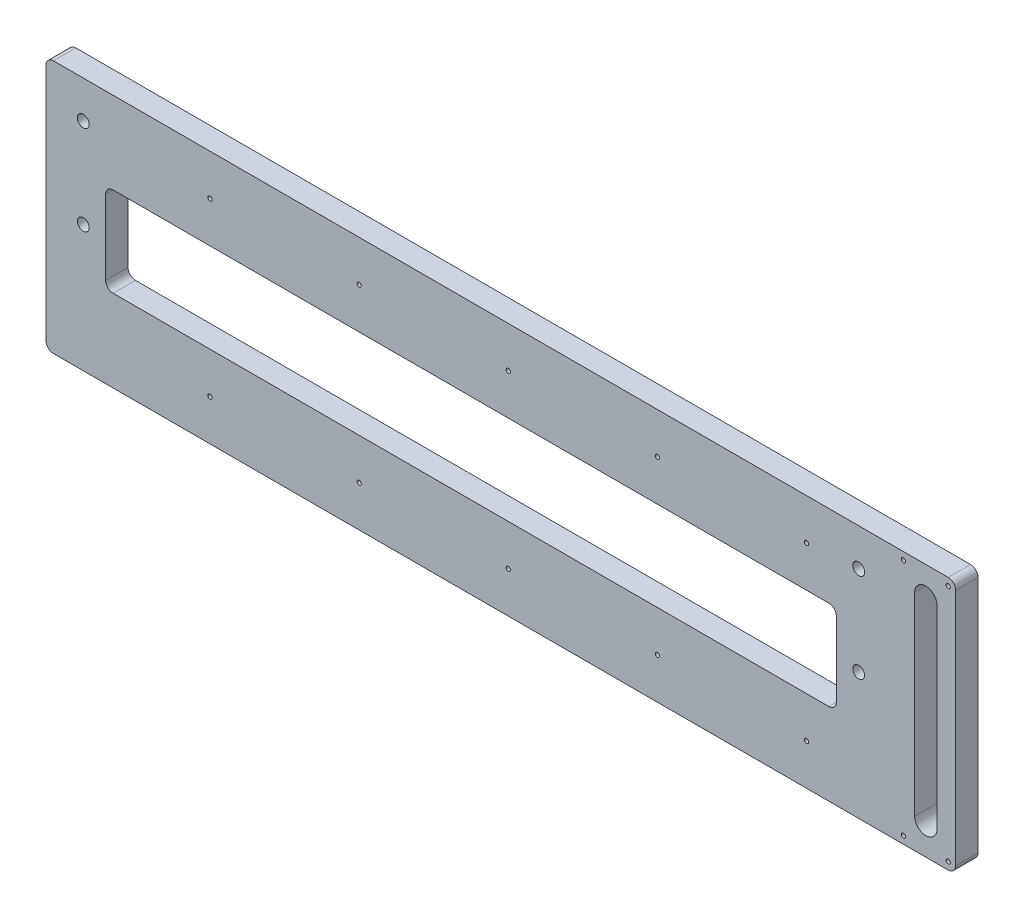
SolidWorks part; units mm, degrees
ref_plane "Front Plane" through (0, 0, 0) normal (0, 0, 1) x (1, 0, 0)
ref_plane "Top Plane" through (0, 0, 0) normal (0, 1, 0) x (1, 0, 0)
ref_plane "Right Plane" through (0, 0, 0) normal (1, 0, 0) x (0, 0, -1)
sketch "Sketch2" plane through (0, 0, 0) normal (0, 0, 1) x (1, 0, 0)
  line L0 (330.2, 107.95) -> (330.2, -107.95)
  line L1 (-393.7, -107.95) -> (330.2, -107.95)
  line L2 (-393.7, -107.95) -> (-393.7, 107.95)
  line L3 (-393.7, 107.95) -> (330.2, 107.95)
  line L5 (-393.7, -107.95) -> (393.7, 107.95) construction
  line L6 (-393.7, 107.95) -> (393.7, -107.95) construction
  point P0 (0, 0)
  dimension "D1" = 787.4
  dimension "D2" = 215.9
extrude "Boss-Extrude1" add sketch "Sketch2" along normal blind 19.05
sketch "Sketch13" plane through (0, 0, 19.05) normal (0, 0, 1) x (1, 0, 0)
  line L1 (-336.55, -38.1) -> (273.05, -38.1)
  line L2 (-342.9, -31.75) -> (-342.9, 31.75)
  line L3 (-336.55, 38.1) -> (273.05, 38.1)
  line L4 (279.4, -31.75) -> (279.4, 31.75)
  line L5 (-342.9, -38.1) -> (279.4, 38.1) construction
  line L6 (-342.9, 38.1) -> (279.4, -38.1) construction
  line L7 (-393.7, 107.95) -> (-393.7, -107.95) construction
  line L9 (330.2, -107.95) -> (330.2, 107.95) construction
  arc A0 (273.05, 38.1) -> (279.4, 31.75) centre (273.05, 31.75) cw
  arc A1 (273.05, -38.1) -> (279.4, -31.75) centre (273.05, -31.75) ccw
  arc A2 (-336.55, -38.1) -> (-342.9, -31.75) centre (-336.55, -31.75) cw
  arc A3 (-342.9, 31.75) -> (-336.55, 38.1) centre (-336.55, 31.75) cw
  point P19 (279.4, 0)
  dimension "D3" = 6.35
  dimension "D1" = 76.2
  dimension "D2" = 50.8
  dimension "D4" = 50.8
extrude "Cut-Extrude3" cut sketch "Sketch13" against normal through all
hole_wizard "#27 (0.144) Diameter Hole1" positions "Sketch14" profile "Sketch15" hole size "#27" standard "ANSI Inch" end condition through all
sketch "Sketch14" plane through (0, 0, 0) normal (0, 0, -1) x (-1, 0, 0)
  line L1 (-254, -73.025) -> (254, -73.025) construction
  line L2 (-254, -73.025) -> (-254, 73.025) construction
  line L3 (-254, 73.025) -> (254, 73.025) construction
  line L4 (254, -73.025) -> (254, 73.025) construction
  line L5 (-254, -73.025) -> (254, 73.025) construction
  line L6 (-254, 73.025) -> (254, -73.025) construction
  point P1 (0, 0)
  point P22 (-254, 73.025)
  point P36 (-127, 73.025)
  point P37 (0, 73.025)
  point P38 (127, 73.025)
  point P39 (254, 73.025)
  point P40 (-127, -73.025)
  point P41 (0, -73.025)
  point P42 (127, -73.025)
  point P43 (254, -73.025)
  point P44 (-254, -73.025)
  dimension "D1" = 146.05
  dimension "D2" = 508
  dimension "D3" = 5
  dimension "D4" = 2
sketch "Sketch15" plane through (0, 0, 0) normal (1, 0, 0) x (0, 1, 0)
  line L0 (0, 0) -> (0, 19.05)
  line L1 (0, 19.05) -> (1.8288, 19.05)
  line L2 (1.8288, 19.05) -> (1.8288, 0)
  line L5 (1.8288, 0) -> (0, 0)
  line L11 (0, -6.35) -> (0, 107.95) construction
  dimension "Thru Hole Dia." = 3.6576
  dimension "Thru Hole Depth" = 19.05
hole_wizard "3/8 Clearance Hole1" positions "Sketch18" profile "Sketch19" hole size "3/8" standard "ANSI Inch" end condition through all
sketch "Sketch18" plane through (0, 0, 0) normal (0, 0, -1) x (-1, 0, 0)
  line L0 (-330.2, -107.95) -> (-330.2, 107.95) construction
  line L1 (-330.2, 107.95) -> (393.7, 107.95) construction
  line L2 (393.7, 107.95) -> (393.7, -107.95) construction
  line L5 (-298.45, 76.2) -> (361.95, 76.2) construction
  line L6 (-298.45, 76.2) -> (-298.45, 0) construction
  line L7 (-298.45, 0) -> (361.95, 0) construction
  line L8 (361.95, 76.2) -> (361.95, 0) construction
  point P0 (-298.45, 76.2)
  point P2 (361.95, 76.2)
  point P73 (361.95, 0)
  point P128 (-298.45, 0)
  dimension "D1" = 31.75
  dimension "D2" = 31.75
  dimension "D3" = 31.75
  dimension "D4" = 31.75
  dimension "D5" = 76.2
sketch "Sketch19" plane through (298.45, 76.2, 0) normal (1, 0, 0) x (0, 1, 0)
  line L0 (0, 0) -> (0, 19.05)
  line L1 (0, 19.05) -> (5.0419, 19.05)
  line L2 (5.0419, 19.05) -> (5.0419, 0)
  line L5 (5.0419, 0) -> (0, 0)
  line L11 (0, -6.35) -> (0, 107.95) construction
  dimension "Thru Hole Dia." = 10.0838
  dimension "Thru Hole Depth" = 19.05
sketch "Sketch22" plane through (330.2, 0, 0) normal (1, 0, 0) x (0, 0, -1)
  line L1 (-19.05, 107.95) -> (0, 107.95)
  line L2 (-19.05, 107.95) -> (-19.05, -107.95)
  line L3 (-19.05, -107.95) -> (0, -107.95)
  line L4 (0, 107.95) -> (0, -107.95)
extrude "Boss-Extrude2" add sketch "Sketch22" along normal blind 50.8
fillet "Fillet1" radius 6.35 4 edges at (-393.7, -107.95, 9.525) (-393.7, 107.95, 9.525) (381, -107.95, 9.525) (381, 107.95, 9.525)
hole_wizard "#6 Clearance Hole1" positions "Sketch23" profile "Sketch24" hole size "#6" standard "ANSI Inch" end condition through all
sketch "Sketch23" plane through (0, 0, 19.05) normal (0, 0, 1) x (1, 0, 0)
  line L0 (355.6, 107.95) -> (355.6, -107.95) construction
  line L1 (374.65, 107.95) -> (-387.35, 107.95) construction
  line L2 (-387.35, -107.95) -> (374.65, -107.95) construction
  line L4 (381, 101.6) -> (381, -101.6) construction
  line L6 (374.65, -101.6) -> (336.55, -101.6) construction
  line L7 (374.65, -101.6) -> (374.65, 101.6) construction
  line L8 (374.65, 101.6) -> (336.55, 101.6) construction
  line L9 (336.55, -101.6) -> (336.55, 101.6) construction
  line L10 (374.65, -101.6) -> (336.55, 101.6) construction
  line L11 (374.65, 101.6) -> (336.55, -101.6) construction
  point P9 (355.6, 0)
  point P10 (336.55, 101.6)
  point P55 (374.65, -101.6)
  point P56 (374.65, 101.6)
  point P57 (336.55, -101.6)
  dimension "D1" = 25.4
  dimension "D2" = 203.2
  dimension "D3" = 38.1
sketch "Sketch24" plane through (336.55, -101.6, 19.05) normal (1, 0, 0) x (0, -1, 0)
  line L0 (0, 0) -> (0, 19.05)
  line L1 (0, 19.05) -> (1.8288, 19.05)
  line L2 (1.8288, 19.05) -> (1.8288, 0)
  line L5 (1.8288, 0) -> (0, 0)
  line L11 (0, -6.35) -> (0, 107.95) construction
  dimension "Thru Hole Dia." = 3.6576
  dimension "Thru Hole Depth" = 19.05
sketch "Sketch25" plane through (0, 0, 19.05) normal (0, 0, 1) x (1, 0, 0)
  line L0 (336.55, 101.6) -> (374.65, -101.6) construction
  line L1 (355.6, -82.55) -> (355.6, 82.55) construction
  line L2 (346.075, -82.55) -> (346.075, 82.55)
  line L3 (365.125, -82.55) -> (365.125, 82.55)
  arc A0 (346.075, -82.55) -> (365.125, -82.55) centre (355.6, -82.55) ccw
  arc A1 (365.125, 82.55) -> (346.075, 82.55) centre (355.6, 82.55) ccw
  point P6 (355.6, 0)
  dimension "D1" = 19.05
  dimension "D2" = 165.1
extrude "Cut-Extrude4" cut sketch "Sketch25" against normal blind 76.2
